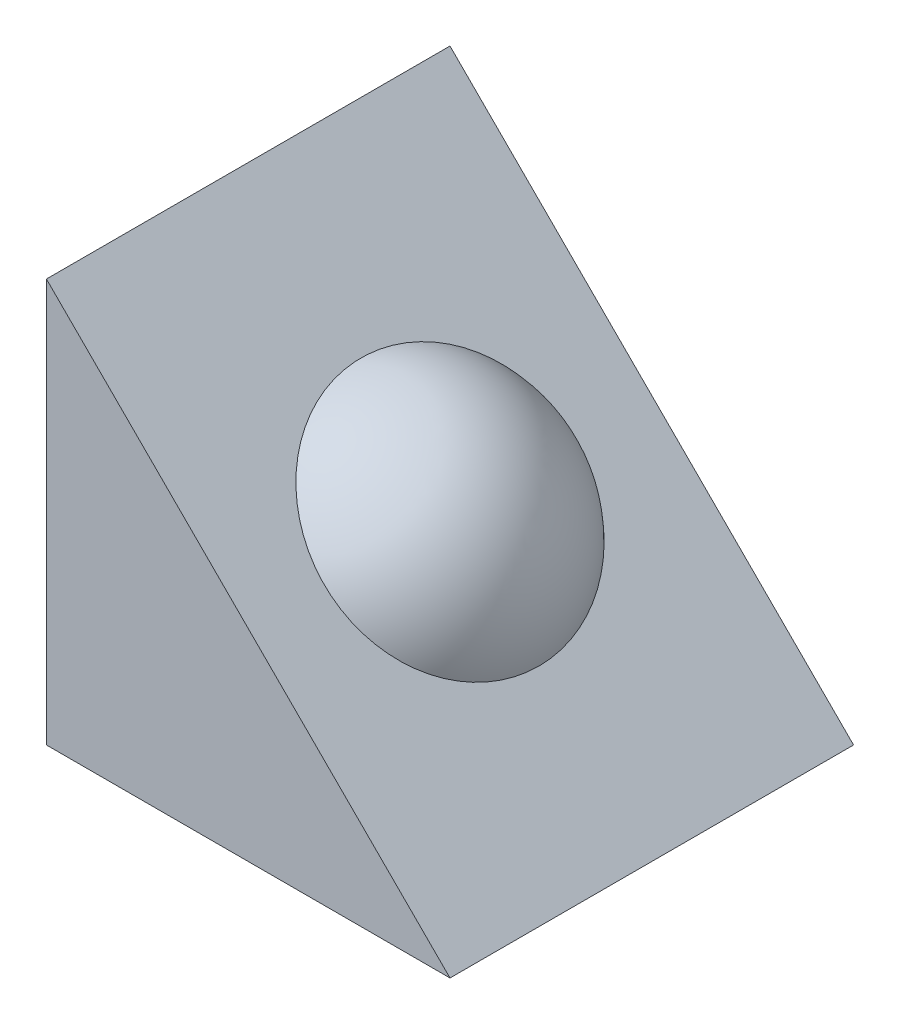
SolidWorks part; units mm, degrees
ref_plane "Front Plane" through (0, 0, 0) normal (0, 0, 1) x (1, 0, 0)
ref_plane "Top Plane" through (0, 0, 0) normal (0, 1, 0) x (1, 0, 0)
ref_plane "Right Plane" through (0, 0, 0) normal (1, 0, 0) x (0, 0, -1)
sketch "Sketch1" plane through (0, 0, 0) normal (0, 0, 1) x (1, 0, 0)
  line L0 (0, 0) -> (0, 50)
  line L1 (0, 0) -> (50, 0)
  line L2 (0, 50) -> (50, 0)
  dimension "D1" = 50
  dimension "D2" = 50
extrude "Boss-Extrude1" add sketch "Sketch1" along normal mid plane 50
sketch "Sketch2" plane through (0, 0, 0) normal (0, 0, 1) x (1, 0, 0)
  line L0 (0, 0) -> (25, 25) construction
  line L1 (50, 0) -> (0, 50) construction
  line L2 (5.9081, 31.364) -> (31.364, 5.9081)
  arc A0 (5.9081, 31.364) -> (31.364, 5.9081) centre (18.636, 18.636) cw
  point P8 (18.3343, 18.3343)
  point P9 (18.636, 18.636)
  dimension "D3" = 18
  dimension "D1" = 36
  dimension "D2" = 9
revolve "Revolve1" add sketch "Sketch2" angle 360 about L2
